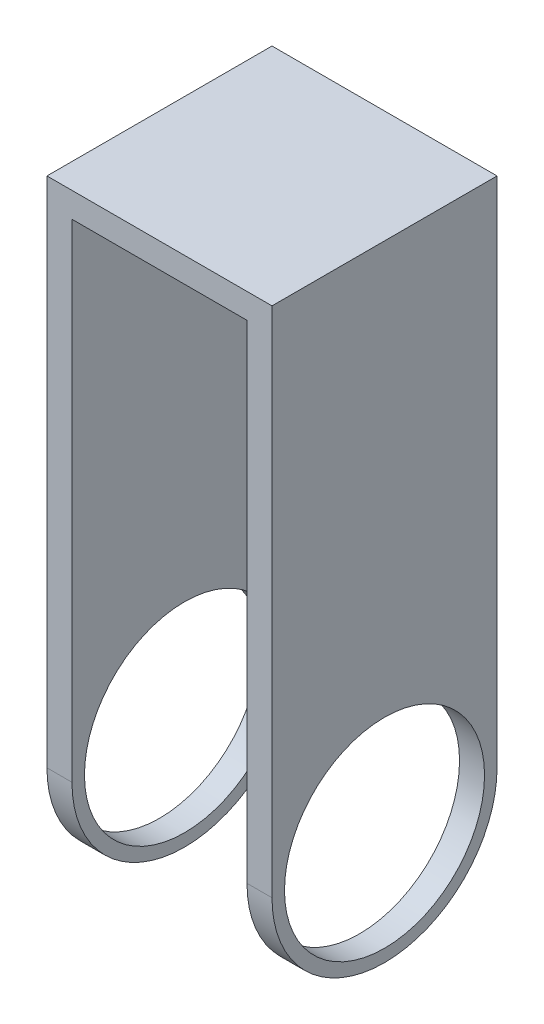
SolidWorks part; units mm, degrees
ref_plane "Front Plane" through (0, 0, 0) normal (0, 0, 1) x (1, 0, 0)
ref_plane "Top Plane" through (0, 0, 0) normal (0, 1, 0) x (1, 0, 0)
ref_plane "Right Plane" through (0, 0, 0) normal (1, 0, 0) x (0, 0, -1)
sketch "Sketch1" plane through (0, 0, 0) normal (0, 1, 0) x (1, 0, 0)
  line L1 (-4, 4.5) -> (4, 4.5)
  line L2 (-4, 4.5) -> (-4, -4.5)
  line L3 (-4, -4.5) -> (4, -4.5)
  line L4 (4, 4.5) -> (4, -4.5)
  line L5 (-4, 4.5) -> (4, -4.5) construction
  line L6 (-4, -4.5) -> (4, 4.5) construction
  point P0 (0, 0)
  dimension "D1" = 8
  dimension "D2" = 9
extrude "Boss-Extrude1" add sketch "Sketch1" along normal blind 1
ref_plane "Plane1" through (4, 0, 0) normal (-1, 0, 0) x (0, 0, 1)
sketch "Sketch6" plane through (4, 0, 0) normal (-1, 0, 0) x (0, 0, 1)
  line L0 (4.5, 1) -> (4.5, -19.5)
  line L1 (4.5, 1) -> (-4.5, 1)
  line L2 (-4.5, 1) -> (-4.5, -19.5)
  line L3 (0, 0) -> (0, -42.1068) construction
  line L4 (4.5, 0) -> (-4.5, 0) construction
  arc A0 (-4.5, -19.5) -> (4.5, -19.5) centre (0, -19.5) ccw
  circle A1 centre (0, -19.5) radius 4
  dimension "D1" = 20.5
  dimension "D2" = 8
extrude "Boss-Extrude2" add sketch "Sketch6" along normal blind 1
ref_plane "Plane2" through (-4, 0, 0) normal (1, 0, 0) x (0, 0, -1)
sketch "Sketch9" plane through (-4, 0, 0) normal (1, 0, 0) x (0, 0, -1)
  line L0 (-4.5, 1) -> (-4.5, -19.5)
  line L1 (-4.5, 1) -> (4.5, 1)
  line L2 (4.5, 1) -> (4.5, -19.5)
  arc A0 (-4.5, -19.5) -> (4.5, -19.5) centre (0, -19.5) ccw
  circle A1 centre (0, -19.5) radius 4
  dimension "D1" = 8
extrude "Boss-Extrude3" add sketch "Sketch9" against normal blind 1
